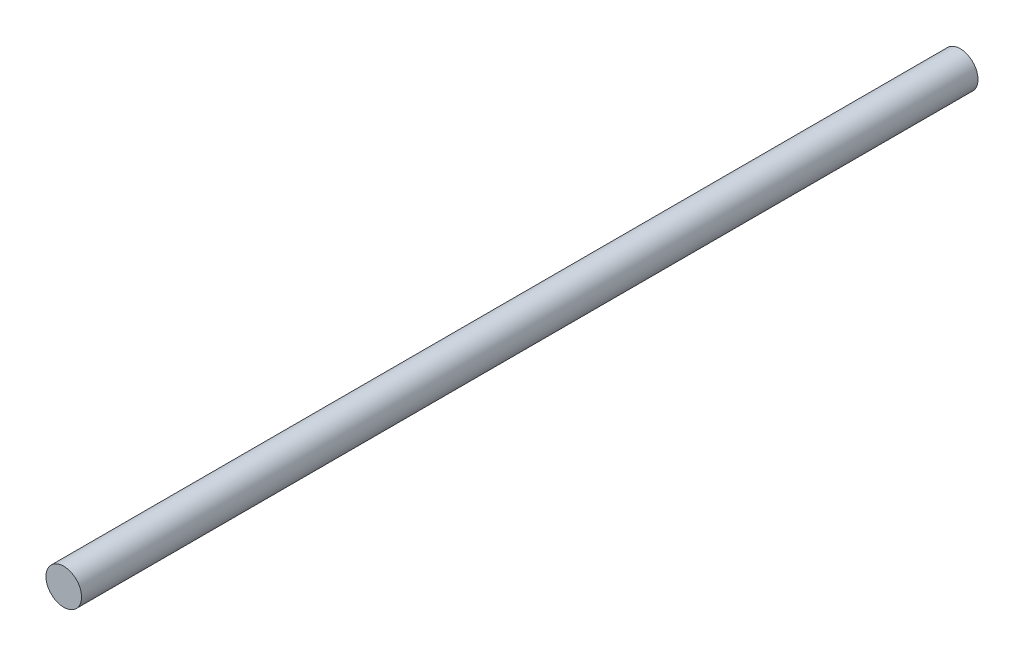
SolidWorks part; units mm, degrees
ref_plane "Front Plane" through (0, 0, 0) normal (0, 0, 1) x (1, 0, 0)
ref_plane "Top Plane" through (0, 0, 0) normal (0, 1, 0) x (1, 0, 0)
ref_plane "Right Plane" through (0, 0, 0) normal (1, 0, 0) x (0, 0, -1)
sketch "Sketch1" plane through (0, 0, 0) normal (0, 0, 1) x (1, 0, 0)
  circle A0 centre (0, 0) radius 0.7937
extrude "Boss-Extrude1" add sketch "Sketch1" along normal blind 40
